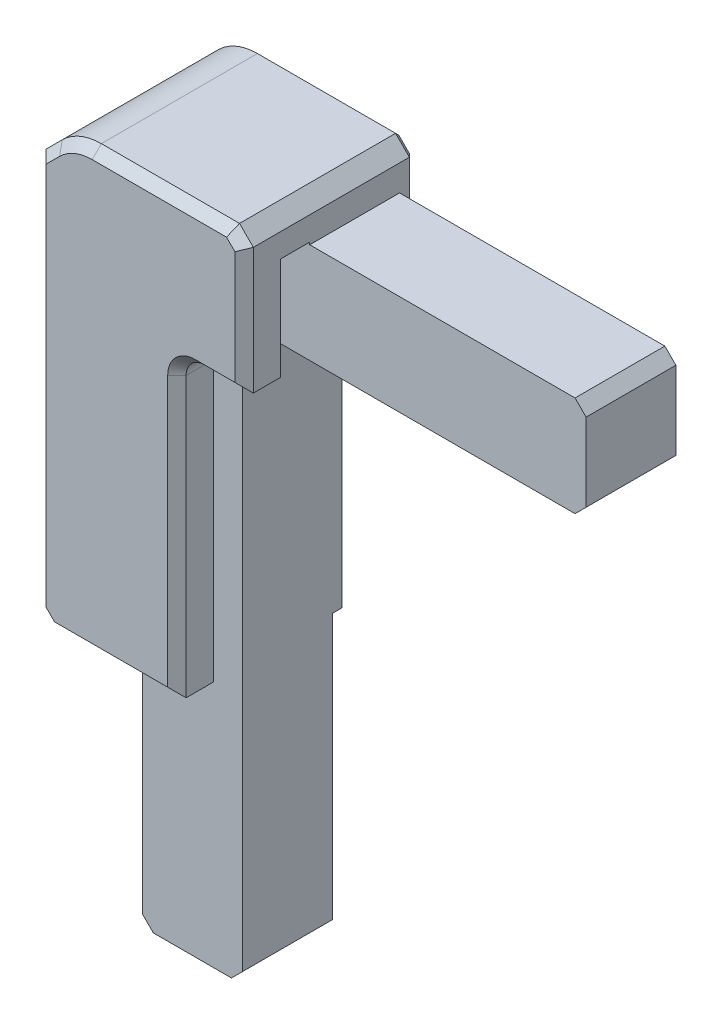
SolidWorks part; units mm, degrees
ref_plane "Front Plane" through (0, 0, 0) normal (0, 0, 1) x (1, 0, 0)
ref_plane "Top Plane" through (0, 0, 0) normal (0, 1, 0) x (1, 0, 0)
ref_plane "Right Plane" through (0, 0, 0) normal (1, 0, 0) x (0, 0, -1)
ref_plane "PZ 19.540" through (0, 0, 19.54) normal (0, 0, 1) x (1, 0, 0)
sketch "body sketch" plane through (0, 0, 19.54) normal (0, 0, 1) x (1, 0, 0)
  line L0 (-4.42, 7.07) -> (18.08, 7.07)
  line L1 (18.08, 7.07) -> (18.08, -8.13)
  line L2 (18.08, -8.13) -> (10.78, -8.13)
  line L3 (10.78, -8.13) -> (10.78, -40.43)
  line L4 (10.78, -40.43) -> (-4.42, -40.43)
  line L5 (-4.42, -40.43) -> (-4.42, 7.07)
extrude "body" add sketch "body sketch" along normal mid plane 11.42
ref_plane "PZ 20.375" through (0, 0, 20.375) normal (0, 0, 1) x (1, 0, 0)
sketch "side tongue sketch" plane through (0, 0, 20.375) normal (0, 0, 1) x (1, 0, 0)
  line L0 (10.78, -70.43) -> (-0.1, -70.43)
  line L1 (-0.1, -70.43) -> (-0.1, -39.43)
  line L2 (-0.1, -39.43) -> (10.78, -39.43)
  line L3 (10.78, -39.43) -> (10.78, -70.43)
extrude "side tongue" add sketch "side tongue sketch" along normal mid plane 9.75
sketch "end tongue sketch" plane through (0, 0, 20.375) normal (0, 0, 1) x (1, 0, 0)
  line L0 (48.08, -8.13) -> (17.08, -8.13)
  line L1 (17.08, -8.13) -> (17.08, 2.75)
  line L2 (17.08, 2.75) -> (48.08, 2.75)
  line L3 (48.08, 2.75) -> (48.08, -8.13)
extrude "end tongue" add sketch "end tongue sketch" along normal mid plane 9.75
ref_plane "PZ 23.100" through (0, 0, 23.1) normal (0, 0, 1) x (1, 0, 0)
sketch "web sketch" plane through (0, 0, 23.1) normal (0, 0, 1) x (1, 0, 0)
  line L0 (-4.42, 7.07) -> (18.08, 7.07)
  line L1 (18.08, 7.07) -> (18.08, 3)
  line L2 (18.08, 3) -> (-0.35, 3)
  line L3 (-0.35, 3) -> (-0.35, -40.43)
  line L4 (-0.35, -40.43) -> (-4.42, -40.43)
  line L5 (-4.42, -40.43) -> (-4.42, 7.07)
extrude "web" add sketch "web sketch" along normal mid plane 18.54
ref_plane "PZ 30.385" through (0, 0, 30.385) normal (0, 0, 1) x (1, 0, 0)
sketch "lip sketch" plane through (0, 0, 30.385) normal (0, 0, 1) x (1, 0, 0)
  line L0 (-4.42, 7.07) -> (18.08, 7.07)
  line L1 (18.08, 7.07) -> (18.08, -8.13)
  line L2 (18.08, -8.13) -> (10.78, -8.13)
  line L3 (10.78, -8.13) -> (10.78, -40.43)
  line L4 (10.78, -40.43) -> (-4.42, -40.43)
  line L5 (-4.42, -40.43) -> (-4.42, 7.07)
extrude "lip" add sketch "lip sketch" along normal mid plane 3.97
ref_plane "PX -0.920" through (-0.92, 0, 0) normal (1, 0, 0) x (0, 0, -1)
sketch "insert holes sketch" plane through (-0.92, 0, 0) normal (1, 0, 0) x (0, 0, -1)
  circle A0 centre (-19.54, -28.7) radius 2.15
  circle A1 centre (-19.54, -12.7) radius 2.15
extrude "insert holes" cut sketch "insert holes sketch" against normal mid plane 9
chamfer "bumper corner, bed side" distance 3.516 angle 45 1 edges at (-4.42, 7.07, 23.1)
fillet "bumper corner" radius 6 1 edges at (-0.904, 7.07, 23.1)
fillet "inside corner of the web" radius 1 1 edges at (-0.35, 3, 26.825)
fillet "reveal corner" radius 2 1 edges at (10.78, -8.13, 30.385)
fillet "body inside corner" radius 2 1 edges at (10.78, -8.13, 19.54)
chamfer "arm ends" distance 1.5 angle 45 2 edges at (18.08, 7.07, 23.1) (-4.42, -40.43, 23.1)
chamfer "tongue lead-in" distance 1.2 angle 45 4 edges at (48.08, -8.13, 20.375) (48.08, 2.75, 20.375) (10.78, -70.43, 20.375) (-0.1, -70.43, 20.375)
chamfer "front face chamfer" distance 1 angle 45 11 edges at (15.43, -8.13, 32.37) (11.3658, -8.7158, 32.37) (10.78, -25.28, 32.37) (3.93, -40.43, 32.37) (-3.67, -39.68, 32.37) (-4.42, -17.688, 32.37) (-3.5407, 4.4333, 32.37) (-0.7148, 6.6133, 32.37) (9.0806, 7.07, 32.37) (17.33, 6.32, 32.37) (18.08, -1.28, 32.37)
chamfer "back face chamfer" distance 0.6 angle 45 11 edges at (-0.7148, 6.6133, 13.83) (-3.5407, 4.4333, 13.83) (-4.42, -17.688, 13.83) (-3.67, -39.68, 13.83) (3.93, -40.43, 13.83) (10.78, -25.28, 13.83) (11.3658, -8.7158, 13.83) (15.43, -8.13, 13.83) (18.08, -1.28, 13.83) (17.33, 6.32, 13.83) (9.0806, 7.07, 13.83)
equation "\"diffL\"= 608.8mm"
equation "\"diffW\"= 329.4mm"
equation "\"diffT\"= 2.9mm"
equation "\"chanSlotW\"= 12.9mm"
equation "\"chanSlotDepth\"= 11.13mm"
equation "\"chanFloor\"= 1.57mm"
equation "\"chanLeg\"= 12.7mm"
equation "\"lightL\"= 605mm"
equation "\"lightW\"= 331mm"
equation "\"lightH\"= 92mm"
equation "\"lightSideFlat\"= 30mm"
equation "\"lightSlopeLen\"= 33.1mm"
equation "\"lightWingDepth\"= 47.9mm"
equation "\"lightWingFlat\"= 90.2mm"
equation "\"lightChanW\"= 99.6mm"
equation "\"lightChanStand\"= 44.1mm"
equation "\"insFlangeD\"= 12.3mm"
equation "\"insFromEnd\"= 20.7mm"
equation "\"insUpSlope\"= 20.8mm"
equation "\"gaugeH\"= 10mm"
equation "\"gaugeStepLen\"= 14mm"
equation "\"gaugeStepW0\"= 13.1mm"
equation "\"gaugeStepDW\"= 0.2mm"
equation "\"gaugeSteps\"= 5mm"
equation "\"gaugeHandleLen\"= 30mm"
equation "\"gaugeHandleW\"= 24mm"
equation "\"gaugeSlot0\"= 3mm"
equation "\"gaugeSlotD\"= 0.1mm"
equation "\"gaugeSlotDepth\"= 8mm"
equation "\"gap\"= 25.4mm"
equation "\"edgeL\"= 1mm"
equation "\"edgeW\"= 0.75mm"
equation "\"proud\"= 1.5mm"
equation "\"seatClr\"= 0.15mm"
equation "\"tongueClrZ\"= 0.1mm"
equation "\"tongueClrX\"= 0.25mm"
equation "\"tongueLen\"= 30mm"
equation "\"armSide\"= 45mm"
equation "\"armEnd\"= 20mm"
equation "\"cornerCham\"= 3mm"
equation "\"brkW\"= 26mm"
equation "\"brkT\"= 7mm"
equation "\"brkSeatClr\"= 0.2mm"
equation "\"brkScrewSpan\"= 16mm"
equation "\"pilotD\"= 2.7mm"
equation "\"pilotDepth\"= 10mm"
equation "\"screwClrD\"= 3.9mm"
equation "\"jogBelow\"= 4mm"
equation "\"padT\"= 7mm"
equation "\"padLen\"= 31mm"
equation "\"m6Clr\"= 7mm"
equation "\"m6Slot\"= 3mm"
equation "\"flangeRelD\"= 17mm"
equation "\"flangeRelDepth\"= 1.5mm"
equation "\"relLen\"= 7mm"
equation "\"relDepth\"= 4mm"
equation "\"relLand\"= 2mm"
equation "\"knockN\"= 100mm"
equation "\"petgcfE\"= 3000mm"
equation "\"mockExtent\"= 110mm"
equation "\"relZnear\"= 9.4mm"
equation "\"relZfar\"= 23.4mm"
equation "\"headD\"= 8mm"
equation "\"headH\"= 2.5mm"
equation "\"headFromEnd\"= 6.8mm"
equation "\"headBack\"= 16.4mm"
equation "\"sideClr\"= 0.4mm"
equation "\"cornerRelR\"= 1.5mm"
equation "\"cornerRelBack\"= 0.6mm"
equation "\"endHeadH\"= 2.8mm"
equation "\"footClr\"= 1.2mm"
equation "\"footEndClr\"= 3.5mm"
equation "\"footLift\"= 6mm"
equation "\"footBlockClr\"= 0.5mm"
equation "\"footBack\"= 50mm"
equation "\"footFwd\"= 10mm"
equation "\"footBraceEnd\"= 3mm"
equation "\"footLoadN\"= 25mm"
equation "\"spacerLen\"= 60mm"
equation "\"spacerShort\"= 0.5mm"
equation "\"spacerCham\"= 0.8mm"
equation "\"spacerPerSide\"= 3mm"
equation "\"spacerPerEnd\"= 1mm"
equation "\"toolR\"= 9mm"
equation "\"visR\"= 4mm"
equation "\"edgeR\"= 1mm"
equation "\"bendOutR\"= 5mm"
equation "\"insideR\"= 2.5mm"
equation "\"footCornerR\"= 10mm"
equation "\"footFrontR\"= 8mm"
equation "\"braceKinkR\"= 12mm"
equation "\"bedCham\"= 1mm"
equation "\"bedChamSmall\"= 0.6mm"
equation "\"soleTopR\"= 2mm"
equation "\"cornerR\"= 6mm"
equation "\"rimInR\"= 1mm"
equation "\"insFlangeH\"= 1mm"
equation "\"insHoleFinishD\"= 4.5mm"
equation "\"insLen\"= 6.4mm"
equation "\"footToeTip\" = 4mm"
equation "\"cgInset\" = 4mm"
equation "\"lampWeightN\" = 51mm"
equation "\"frameWeightN\" = 10mm"
equation "\"bumpIn\" = 8mm"
equation "\"bumpH\" = 3mm"
equation "\"legBelowFront\" = 2mm"
equation "\"lipClr\" = 0.1mm"
equation "\"revealR\" = 2mm"
equation "\"frontCham\" = 1mm"
